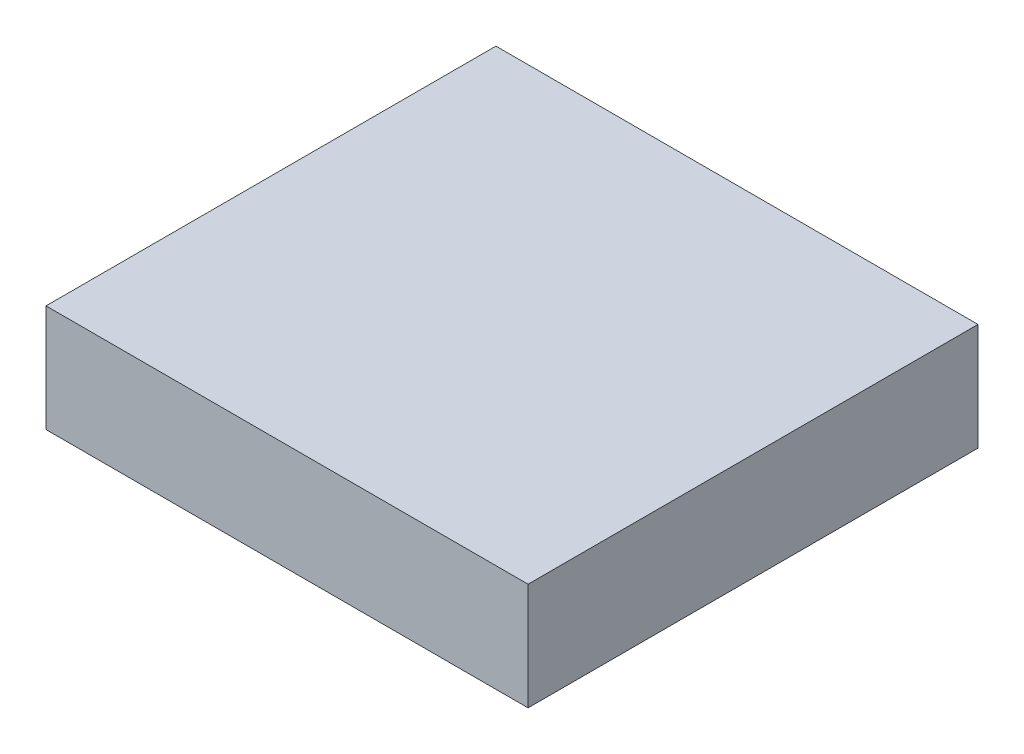
SolidWorks part; units mm, degrees
ref_plane "Alzado" through (0, 0, 0) normal (0, 0, 1) x (1, 0, 0)
ref_plane "Planta" through (0, 0, 0) normal (0, 1, 0) x (1, 0, 0)
ref_plane "Vista lateral" through (0, 0, 0) normal (1, 0, 0) x (0, 0, -1)
sketch "Croquis1" plane through (0, 0, 0) normal (0, 1, 0) x (1, 0, 0)
  line L1 (-22.5, -21) -> (22.5, -21)
  line L2 (-22.5, -21) -> (-22.5, 21)
  line L3 (-22.5, 21) -> (22.5, 21)
  line L4 (22.5, -21) -> (22.5, 21)
  line L5 (-22.5, -21) -> (22.5, 21) construction
  line L6 (-22.5, 21) -> (22.5, -21) construction
  point P0 (0, 0)
  dimension "D1" = 45
  dimension "D2" = 42
extrude "Saliente-Extruir1" add sketch "Croquis1" along normal blind 10
